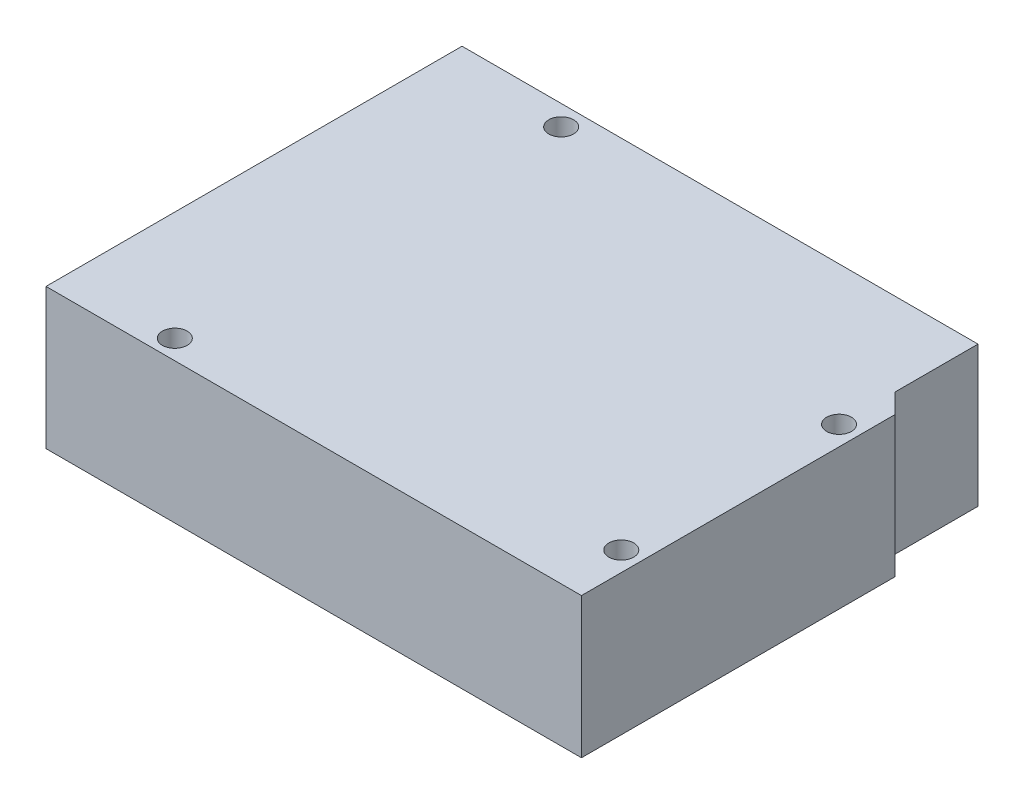
SolidWorks part; units mm, degrees
ref_plane "前视基准面" through (0, 0, 0) normal (0, 0, 1) x (1, 0, 0)
ref_plane "上视基准面" through (0, 0, 0) normal (0, 1, 0) x (1, 0, 0)
ref_plane "右视基准面" through (0, 0, 0) normal (1, 0, 0) x (0, 0, -1)
other "Configuration Table"
sketch "草图1" plane through (0, 0, 0) normal (0, 1, 0) x (1, 0, 0)
  line L0 (-34.3, -24.15) -> (34.3, -24.15) construction
  line L1 (-34.3, 26.65) -> (34.3, 26.65)
  line L2 (-34.3, 26.65) -> (-34.3, -26.65)
  line L3 (-34.3, -26.65) -> (34.3, -26.65)
  line L4 (34.3, 26.65) -> (34.3, -26.65)
  line L5 (0, -26.65) -> (0, 26.65) construction
  line L6 (-34.3, 0) -> (34.3, 0) construction
  line L7 (-20.3, -24.15) -> (-20.3, 26.65) construction
  line L8 (31.8, 26.65) -> (31.8, -26.65) construction
  line L9 (-19, 24.05) -> (31.8, 24.05) construction
  line L10 (31.8, 26.65) -> (31.8, 16.0197)
  line L11 (31.8, 16.0197) -> (34.3, 13.5197)
  circle A0 centre (-20.3, -24.15) radius 1.5875
  circle A3 centre (-19, 24.05) radius 1.5875
  circle A4 centre (31.8, -19.05) radius 1.5875
  circle A5 centre (31.8, 8.85) radius 1.5875
  point P0 (0, 0)
  dimension "D4" = 15.2
  dimension "D10" = 3.175
  dimension "D11" = 3.175
  dimension "D12" = 3.175
  dimension "D13" = 3.175
  dimension "D1" = 68.6
  dimension "D2" = 53.3
  dimension "D3" = 2.5
  dimension "D5" = 27.9
  dimension "D6" = 14
  dimension "D7" = 1.3
  dimension "D8" = 50.8
  dimension "D9" = 5.1
  dimension "D14" = 45
extrude "凸台-拉伸1" add sketch "草图1" along normal blind 18 contours L11 L10 L1 L2 L3 L4 A5 A4 A3 A0
